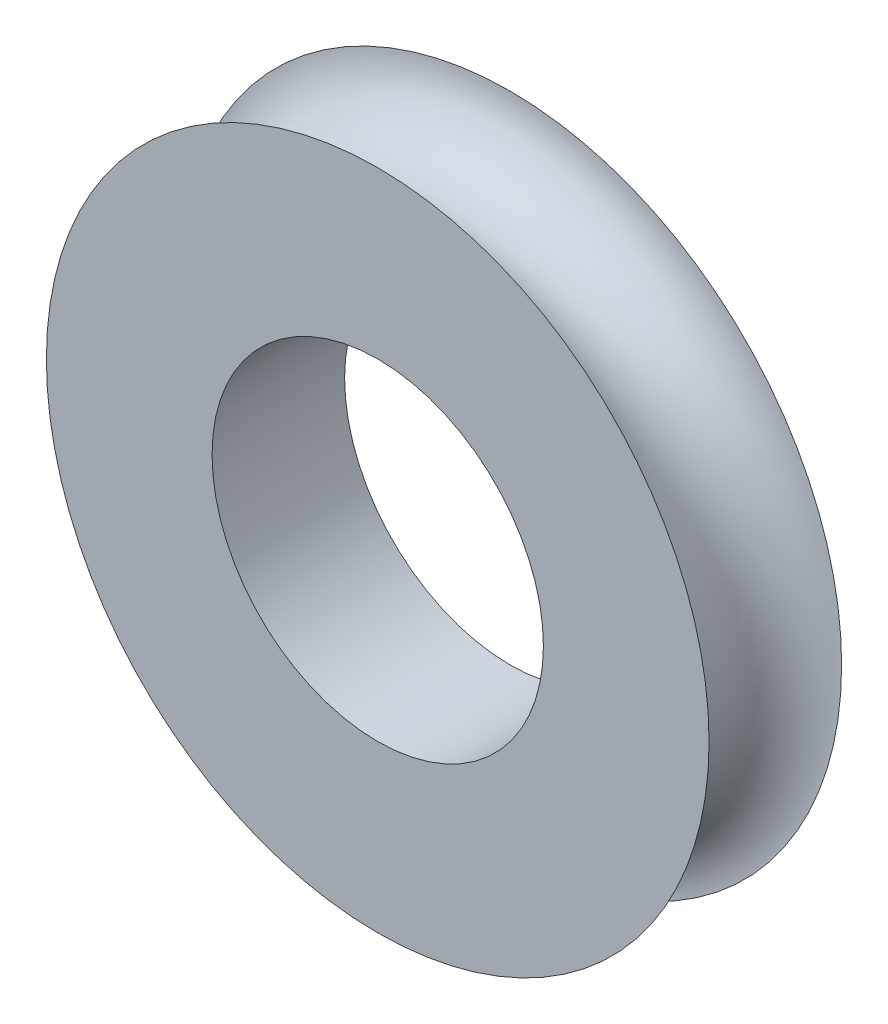
SolidWorks part; units mm, degrees
ref_plane "Front Plane" through (0, 0, 0) normal (0, 0, 1) x (1, 0, 0)
ref_plane "Top Plane" through (0, 0, 0) normal (0, 1, 0) x (1, 0, 0)
ref_plane "Right Plane" through (0, 0, 0) normal (1, 0, 0) x (0, 0, -1)
sketch "Sketch1" plane through (0, 0, 0) normal (0, 0, 1) x (1, 0, 0)
  circle A0 centre (0, 0) radius 5
  circle A1 centre (0, 0) radius 2.5
  dimension "D1" = 10
  dimension "D2" = 5
extrude "Boss-Extrude1" add sketch "Sketch1" along normal blind 2
sketch "Sketch2" plane through (0, 0, 0) normal (1, 0, 0) x (0, 0, -1)
  line L0 (0, 5) -> (-2, 5) construction
  line L1 (-2, 5) -> (0, 5)
  arc A0 (-2, 5) -> (0, 5) centre (-1, 5) ccw
revolve "Cut-Revolve1" cut sketch "Sketch2" angle 360 about axis through (0, 0, 2) along (0, 0, -1)
ref_point "Centre"
equation "\"CableDiameter\"=2"
equation "\"D1@Boss-Extrude1\"=\"CableDiameter\""
